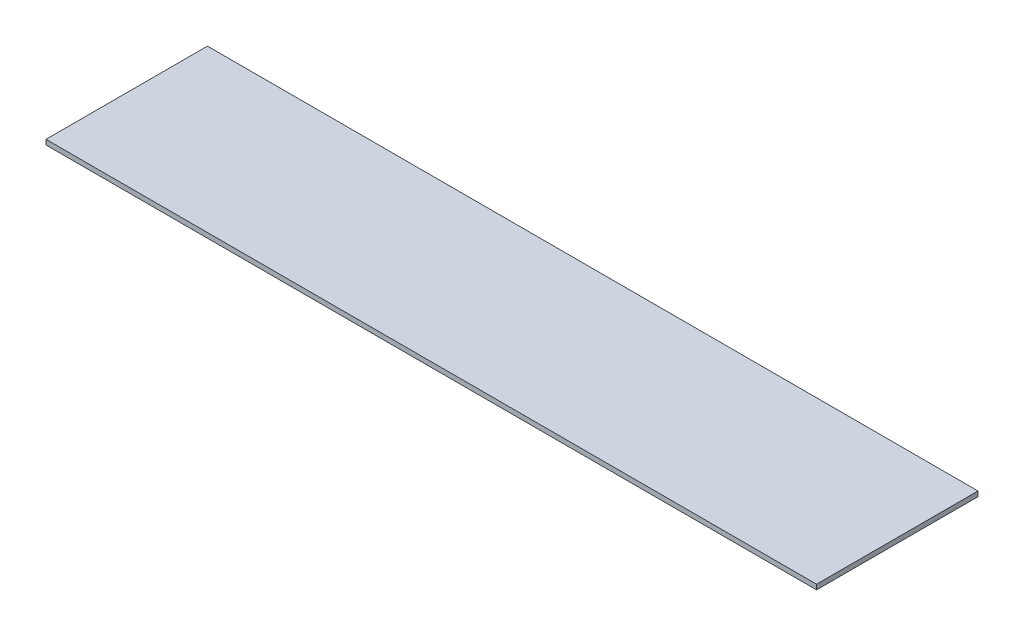
SolidWorks part; units mm, degrees
ref_plane "Front Plane" through (0, 0, 0) normal (0, 0, 1) x (1, 0, 0)
ref_plane "Top Plane" through (0, 0, 0) normal (0, 1, 0) x (1, 0, 0)
ref_plane "Right Plane" through (0, 0, 0) normal (1, 0, 0) x (0, 0, -1)
sketch "Sketch1" plane through (0, 0, 0) normal (0, 1, 0) x (1, 0, 0)
  line L0 (247.65, -51.89) -> (247.65, -8.4528) construction
  line L1 (0, 0) -> (247.65, 0)
  line L2 (0, 0) -> (0, -51.89)
  line L3 (0, -51.89) -> (247.65, -51.89)
  line L4 (247.65, 0) -> (247.65, -51.89)
  line L5 (0, -51.89) -> (12.7, -51.89) construction
  point P5 (225.9619, -74.5867)
extrude "Boss-Extrude1" add sketch "Sketch1" along normal blind 1.5875
